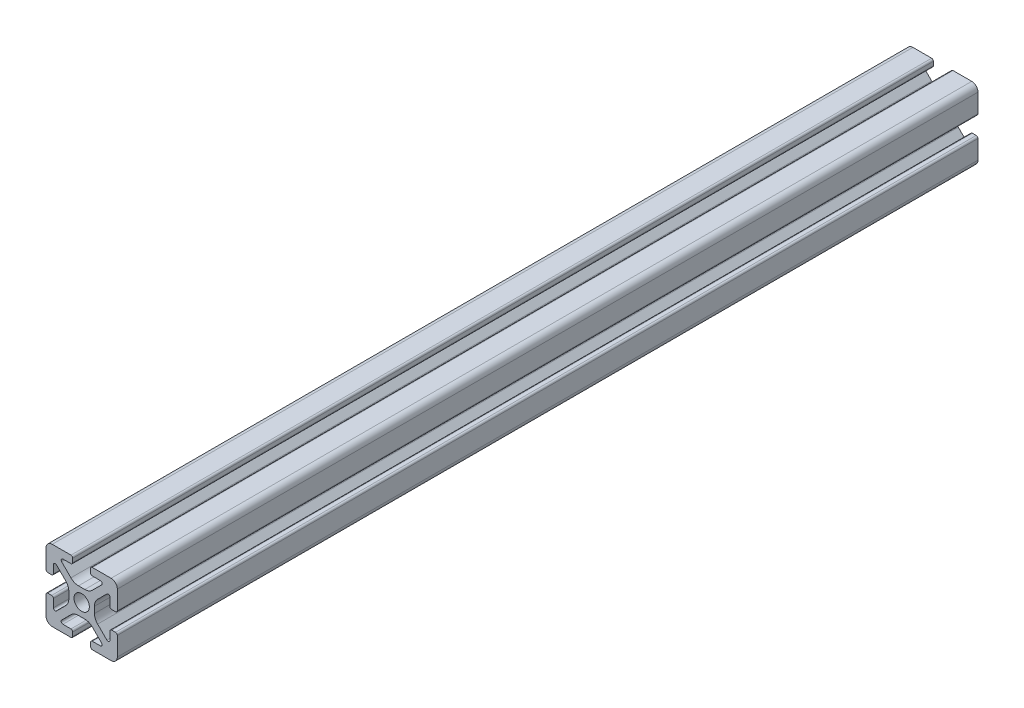
SolidWorks part; units mm, degrees
ref_plane "Front Plane" through (0, 0, 0) normal (0, 0, 1) x (1, 0, 0)
ref_plane "Top Plane" through (0, 0, 0) normal (0, 1, 0) x (1, 0, 0)
ref_plane "Right Plane" through (0, 0, 0) normal (1, 0, 0) x (0, 0, -1)
sketch "Sketch2" plane through (0, 0, 0) normal (0, 0, 1) x (1, 0, 0)
  line L0 (0, 10) -> (0, -10) construction
  line L1 (-10, 0) -> (10, 0) construction
  line L2 (2.5, -10) -> (10, -10)
  line L3 (10, -10) -> (10, -2.5)
  line L4 (2.5, -10) -> (2.5, -7.9246)
  line L5 (2.5, -7.9246) -> (6.4571, -7.9246)
  line L6 (6.4571, -7.9246) -> (2.1325, -3.6)
  line L7 (0, 0) -> (10, -10) construction
  line L8 (10, -2.5) -> (7.9246, -2.5)
  line L9 (7.9246, -2.5) -> (7.9246, -6.4571)
  line L10 (7.9246, -6.4571) -> (3.6, -2.1325)
  line L11 (5.7623, -4.2948) -> (4.2948, -5.7623) construction
  circle A0 centre (0, 0) radius 2.15
  arc A1 (5.25, -7.9246) -> (5.6036, -7.0711) centre (5.25, -7.4246) ccw construction
  point P8 (0, -3.6)
  point P16 (5.0286, -5.0286)
  dimension "Center Hole Diameter" = 4.3
  dimension "D3" = 0.5
  dimension "Rail Height" = 20
  dimension "Rail Width" = 20
  dimension "T-Slot Width" = 5
  dimension "Slot Depth" = 6.4
  dimension "Slot Inner Width" = 11.5
sketch "Sketch3" plane through (0, 0, 0) normal (1, 0, 0) x (0, 0, -1)
  line L0 (-457.2, -10) -> (457.2, -10) construction
  line L1 (-431.8, 0) -> (431.8, 0) construction
  line L2 (0, 10) -> (0, -10) construction
  line L3 (0, 10) -> (0, -10) construction
  point P6 (-431.8, 0)
  point P8 (431.8, 0)
  dimension "Length" = 914.4
  dimension "D1" = 25.4
sketch "Sketch4" plane through (0, 0, 0) normal (0, 0, 1) x (1, 0, 0)
  line L0 (3, -10) -> (8.25, -10)
  line L1 (2.5, -10) -> (10, -10) construction
  line L2 (2.5, -10) -> (2.5, -7.9246) construction
  line L3 (2.5, -7.9246) -> (6.4571, -7.9246) construction
  line L4 (2.5, -8.4246) -> (2.5, -9.5)
  line L5 (3, -7.9246) -> (5.25, -7.9246)
  line L6 (0, -3.6) -> (0.8898, -3.6)
  line L7 (6.4571, -7.9246) -> (2.1325, -3.6) construction
  line L8 (3.0112, -4.4787) -> (5.6036, -7.0711)
  line L9 (10, -10) -> (10, -2.5) construction
  line L10 (7.9246, -6.4571) -> (3.6, -2.1325) construction
  line L11 (7.9246, -2.5) -> (7.9246, -6.4571) construction
  line L12 (7.9246, -5.25) -> (7.9246, -3)
  line L13 (10, -2.5) -> (7.9246, -2.5) construction
  line L14 (8.4246, -2.5) -> (9.5, -2.5)
  line L15 (10, -3) -> (10, -8.25)
  line L16 (7.0711, -5.6036) -> (4.4787, -3.0112)
  line L17 (3.6, 0) -> (3.6, -0.8898)
  line L18 (-10, 0) -> (10, 0) construction
  line L19 (0, -3.6) -> (0, -2.15)
  line L20 (0, 10) -> (0, -10) construction
  line L21 (3.6, 0) -> (2.15, 0)
  arc A0 (2.5, -9.5) -> (3, -10) centre (3, -9.5) ccw
  arc A1 (5.25, -7.9246) -> (5.6036, -7.0711) centre (5.25, -7.4246) ccw construction
  arc A2 (2.5, -8.4246) -> (3, -7.9246) centre (3, -8.4246) cw
  arc A3 (5.25, -7.9246) -> (5.6036, -7.0711) centre (5.25, -7.4246) ccw
  arc A4 (0.8898, -3.6) -> (3.0112, -4.4787) centre (0.8898, -6.6) cw
  arc A5 (8.25, -10) -> (10, -8.25) centre (8.25, -8.25) ccw
  arc A6 (7.0711, -5.6036) -> (7.9246, -5.25) centre (7.4246, -5.25) ccw
  arc A7 (7.9246, -3) -> (8.4246, -2.5) centre (8.4246, -3) cw
  arc A8 (9.5, -2.5) -> (10, -3) centre (9.5, -3) cw
  arc A9 (4.4787, -3.0112) -> (3.6, -0.8898) centre (6.6, -0.8898) cw
  circle A10 centre (0, 0) radius 2.15 construction
  arc A11 (0, -2.15) -> (2.15, 0) centre (0, 0) ccw
  dimension "D1" = 1.75
  dimension "D2" = 3
extrude "Boss-Extrude1" add sketch "Sketch4" along normal mid plane 181
mirror "Mirror1" about plane through (0, 0, 0) normal (1, 0, 0) of bodies 134
mirror "Mirror2" about plane through (0, 0, 0) normal (0, 1, 0) of bodies 135
scale "Scale1" bodies to scale 136 scale about centroid uniform scaling no x scale factor 0.75 y scale factor 0.75 z scale factor 1
equation "\"D3@Sketch2\"=\"T-Slot Width@Sketch2\"*0.1"
equation "\"D1@Sketch4\"=\"D3@Sketch2\"*3.5"
equation "\"D2@Sketch4\"=\"D3@Sketch2\"*6"
equation "\"D1@Boss-Extrude1\"=\"Length@Sketch3\""
